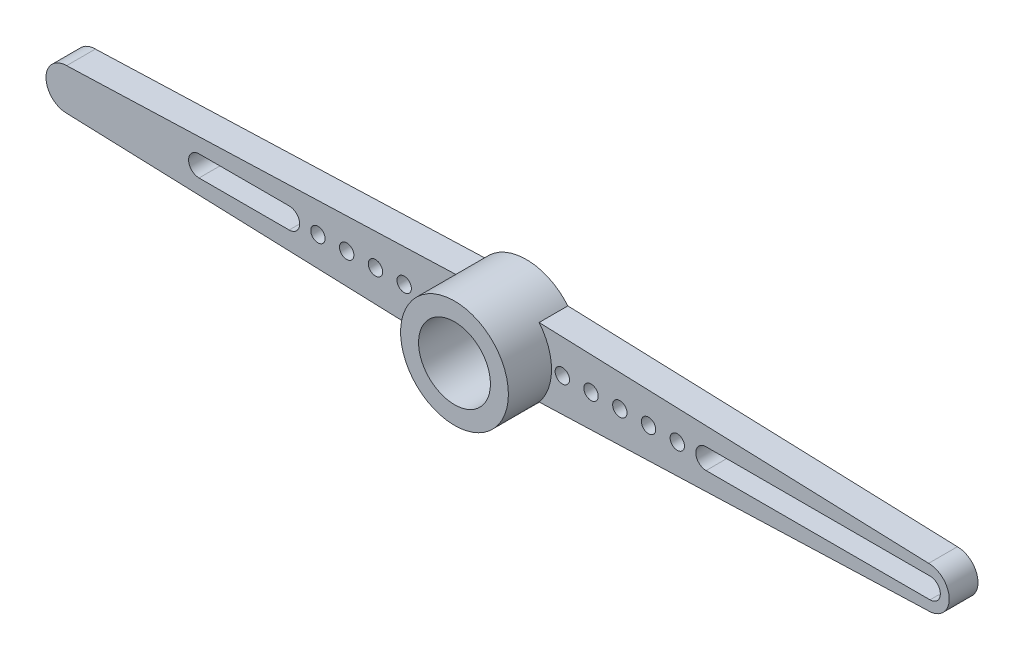
SolidWorks part; units mm, degrees
ref_plane "Спереди" through (0, 0, 0) normal (0, 0, 1) x (1, 0, 0)
ref_plane "Сверху" through (0, 0, 0) normal (0, 1, 0) x (1, 0, 0)
ref_plane "Справа" through (0, 0, 0) normal (1, 0, 0) x (0, 0, -1)
sketch "Эскиз1" plane through (0, 0, 0) normal (0, 0, 1) x (1, 0, 0)
  line L0 (0, 0) -> (-14, 0)
  line L1 (-29.9812, 1.4349) -> (0, 2.4974)
  line L2 (-29.9812, -1.4349) -> (0, -2.4974)
  line L4 (29.9812, -1.4349) -> (0, -2.4974)
  line L5 (29.9812, 1.4349) -> (0, 2.4974)
  circle A0 centre (0, 0) radius 3.75
  circle A1 centre (0, 0) radius 2.5
  arc A2 (-29.9812, -1.4349) -> (-29.9812, 1.4349) centre (-29.9812, 0) cw
  arc A3 (29.9812, -1.4349) -> (29.9812, 1.4349) centre (29.9812, 0) ccw
  dimension "D1" = 7.5
  dimension "D2" = 5
  dimension "D3" = 14
extrude "Бобышка-Вытянуть3" add sketch "Эскиз1" along normal blind 2
sketch "Эскиз2" plane through (0, 0, 2) normal (0, 0, 1) x (1, 0, 0)
  circle A0 centre (0, 0) radius 3.75
  circle A1 centre (0, 0) radius 2.5
  dimension "D1" = 5
extrude "Бобышка-Вытянуть5" add sketch "Эскиз2" along normal blind 3 separate body
sketch "Эскиз3" plane through (0, 0, 2) normal (0, 0, -1) x (-1, 0, 0)
  circle A0 centre (0, 0) radius 3.75
  circle A1 centre (0, 0) radius 2.5
extrude "Бобышка-Вытянуть6" add sketch "Эскиз3" along normal blind 2
sketch "Эскиз4" plane through (0, 0, 0) normal (0, 0, -1) x (-1, 0, 0)
  line L0 (-16, 0) -> (-14.5, 0)
  line L1 (-14.5, 0) -> (-12.5, 0)
  line L2 (-12.5, 0) -> (-10.5, 0)
  line L3 (-10.5, 0) -> (-8.5, 0)
  line L4 (-8.5, 0) -> (-6.5, 0)
  line L5 (-6.5, 0) -> (-4.5, 0)
  arc A0 (-14.0708, 1.9987) -> (-14.0708, -1.9987) centre (-14, 0) ccw construction
  circle A1 centre (-14.5, 0) radius 0.5
  circle A2 centre (-12.5, 0) radius 0.5
  circle A3 centre (-10.5, 0) radius 0.5
  circle A4 centre (-8.5, 0) radius 0.5
  circle A5 centre (-6.5, 0) radius 0.5
  circle A6 centre (-4.5, 0) radius 0.5
  circle A7 centre (4.5, 0) radius 0.5
  circle A8 centre (6.5, 0) radius 0.5
  circle A9 centre (8.5, 0) radius 0.5
  circle A10 centre (10.5, 0) radius 0.5
  circle A11 centre (12.5, 0) radius 0.5
  circle A12 centre (14.5, 0) radius 0.5
  dimension "D2" = 1
  dimension "D8" = 1
  dimension "D9" = 1
  dimension "D10" = 1
  dimension "D11" = 1
  dimension "D12" = 1
  dimension "D1" = 1.5
  dimension "D3" = 2
  dimension "D4" = 2
  dimension "D5" = 2
  dimension "D6" = 2
  dimension "D7" = 2
extrude "Вырез-Вытянуть1" cut sketch "Эскиз4" against normal blind 2
sketch "Эскиз5" plane through (0, 0, 0) normal (0, 0, -1) x (-1, 0, 0)
  circle A0 centre (0, 0) radius 2.5
extrude "Бобышка-Вытянуть7" add sketch "Эскиз5" against normal blind 1
sketch "Эскиз6" plane through (0, 0, 0) normal (0, 0, -1) x (-1, 0, 0)
  circle A0 centre (0, 0) radius 2.5
  dimension "D1" = 5
extrude "Вырез-Вытянуть2" cut sketch "Эскиз6" against normal blind 0.5
sketch "Эскиз7" plane through (0, 0, 0.5) normal (0, 0, -1) x (-1, 0, 0)
  circle A0 centre (0, 0) radius 1.25
  dimension "D1" = 2.5
extrude "Вырез-Вытянуть3" cut sketch "Эскиз7" against normal blind 5
sketch "Эскиз8" plane through (0, 0, 0.5) normal (0, 0, -1) x (-1, 0, 0)
  line L0 (-2.8252, -0.1999) -> (-2.8894, -0.2509)
sketch "Sketch1" plane through (0, 0, 5) normal (0, 0, 1) x (1, 0, 0)
  line L2 (2.8855, -2.3951) -> (29.9812, -1.4349)
  line L3 (29.9812, 1.4349) -> (2.8855, 2.3951)
  line L4 (2.8855, -2.3951) -> (29.9812, -1.4349)
  line L5 (29.9812, 1.4349) -> (2.8855, 2.3951)
  arc A0 (2.8855, -2.3951) -> (2.8855, 2.3951) centre (0, 0) ccw
  arc A3 (2.8855, -2.3951) -> (2.8855, 2.3951) centre (0, 0) ccw
  arc A4 (29.9812, -1.4349) -> (29.9812, 1.4349) centre (29.9812, 0) ccw
  arc A5 (2.8855, -2.3951) -> (2.8855, 2.3951) centre (0, 0) ccw
  arc A7 (29.9812, -1.4349) -> (29.9812, 1.4349) centre (29.9812, 0) ccw
  dimension "D1" = 0
sketch "Sketch3" plane through (0, 0, 0) normal (0, 0, -1) x (-1, 0, 0)
  line L3 (-14.5, 0) -> (-30.0791, 0) construction
  line L6 (20.7703, 0) -> (14.5, 0) construction
  line L7 (20.7703, -0.7267) -> (14.5, -0.7267)
  line L8 (20.7703, 0.7267) -> (14.5, 0.7267)
  line L9 (-14.5, -0.716) -> (-30.0791, -0.716)
  line L10 (-14.5, 0.716) -> (-30.0791, 0.716)
  arc A4 (20.7703, -0.7267) -> (20.7703, 0.7267) centre (20.7703, 0) ccw
  arc A5 (14.5, 0.7267) -> (14.5, -0.7267) centre (14.5, 0) ccw
  arc A6 (-14.5, -0.716) -> (-14.5, 0.716) centre (-14.5, 0) ccw
  arc A7 (-30.0791, 0.716) -> (-30.0791, -0.716) centre (-30.0791, 0) ccw
  point P0 (17.6351, 0)
  point P10 (-22.2896, 0)
extrude "Cut-Extrude2" cut sketch "Sketch3" against normal blind 2
